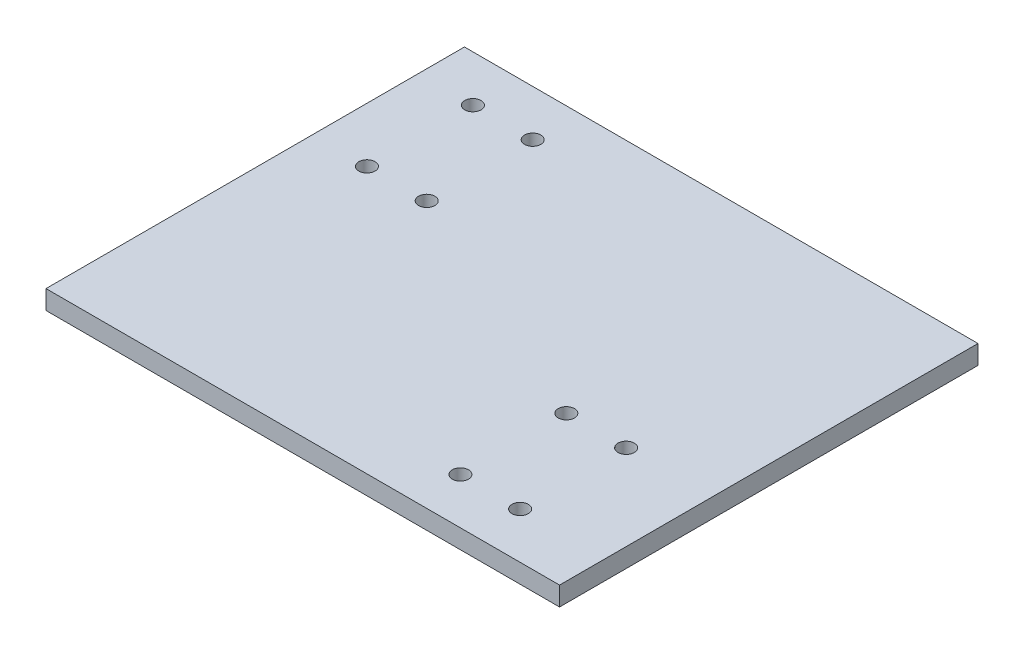
SolidWorks part; units mm, degrees
ref_plane "Front Plane" through (0, 0, 0) normal (0, 0, 1) x (1, 0, 0)
ref_plane "Top Plane" through (0, 0, 0) normal (0, 1, 0) x (1, 0, 0)
ref_plane "Right Plane" through (0, 0, 0) normal (1, 0, 0) x (0, 0, -1)
sketch "Sketch1" plane through (0, 0, 0) normal (0, 1, 0) x (1, 0, 0)
  line L0 (94.5, -77) -> (30, -77)
  line L1 (-94.5, 77) -> (94.5, 77)
  line L2 (-94.5, 77) -> (-94.5, -77)
  line L3 (-94.5, -77) -> (94.5, -77)
  line L4 (94.5, 77) -> (94.5, -77)
  line L5 (30, -60) -> (74, -60) construction
  line L6 (-94.5, -77) -> (94.5, 77) construction
  line L7 (30, -77) -> (30, 77) construction
  line L8 (41, -60) -> (41, -21) construction
  line L9 (63, -60) -> (63, -21) construction
  line L10 (-94.5, 77) -> (-85.39, 77)
  line L11 (-85.39, 77) -> (-85.39, -77) construction
  line L12 (-74.39, 60) -> (-74.39, 21) construction
  line L13 (-85.39, 60) -> (-41.39, 60) construction
  line L14 (-52.39, 60) -> (-52.39, 21) construction
  circle A0 centre (41, -60) radius 3
  circle A1 centre (63, -60) radius 3
  circle A2 centre (41, -21) radius 3
  circle A3 centre (63, -21) radius 3
  circle A4 centre (-74.39, 60) radius 3
  circle A5 centre (-52.39, 60) radius 3
  circle A6 centre (-74.39, 21) radius 3
  circle A7 centre (-52.39, 21) radius 3
  point P0 (0, 0)
  dimension "D8" = 6
  dimension "D9" = 6
  dimension "D10" = 6
  dimension "D12" = 6
  dimension "D18" = 6
  dimension "D19" = 6
  dimension "D22" = 6
  dimension "D23" = 6
  dimension "D1" = 154
  dimension "D2" = 189
  dimension "D3" = 64.5
  dimension "D4" = 17
  dimension "D5" = 44
  dimension "D6" = 39
  dimension "D7" = 22
  dimension "D11" = 39
  dimension "D13" = 9.11
  dimension "D14" = 17
  dimension "D15" = 44
  dimension "D16" = 11
  dimension "D17" = 22
  dimension "D20" = 39
  dimension "D21" = 39
extrude "Boss-Extrude1" add sketch "Sketch1" along normal blind 7 contours L4 L1 L2 L3 L0 A7 A6 A5 A4 A3 A2 A1 A0
